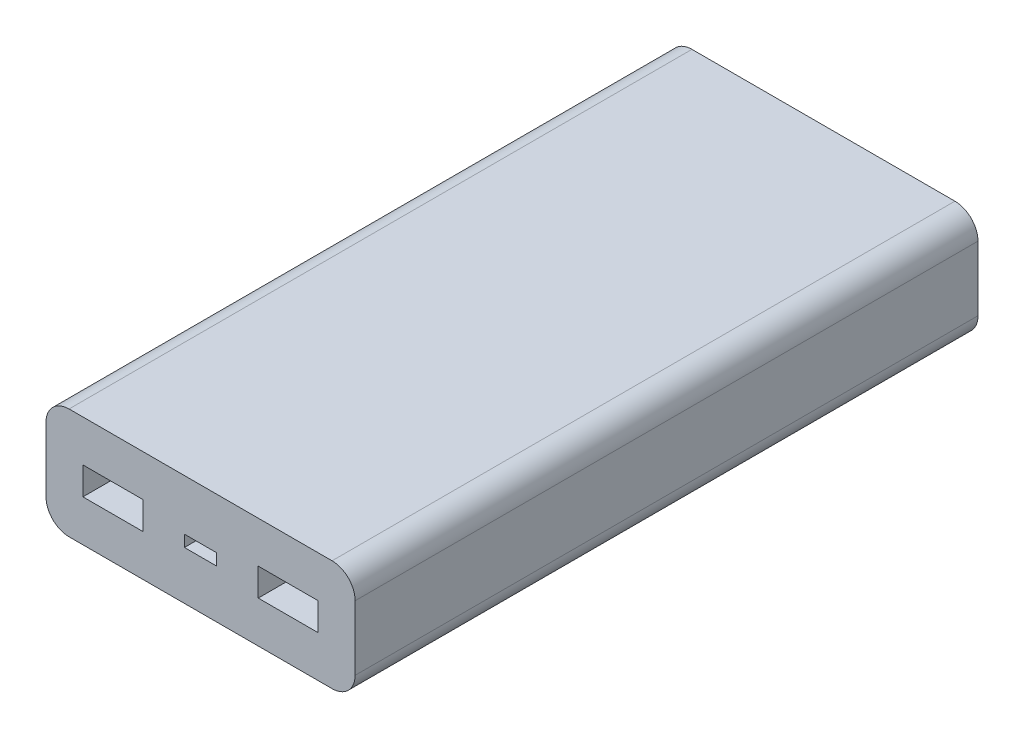
SolidWorks part; units mm, degrees
material "ABS"
ref_plane "Plan de face" through (0, 0, 0) normal (0, 0, 1) x (1, 0, 0)
ref_plane "Plan de dessus" through (0, 0, 0) normal (0, 1, 0) x (1, 0, 0)
ref_plane "Plan de droite" through (0, 0, 0) normal (1, 0, 0) x (0, 0, -1)
sketch "Esquisse1" plane through (0, 0, 0) normal (0, 0, 1) x (1, 0, 0)
  line L1 (0, 0) -> (67, 0)
  line L2 (0, 0) -> (0, 24)
  line L3 (0, 24) -> (67, 24)
  line L4 (67, 0) -> (67, 24)
  dimension "D1" = 67
  dimension "D2" = 24
extrude "Boss.-Extru.1" add sketch "Esquisse1" along normal blind 135
fillet "Congé1" radius 5 4 edges at (0, 0, 67.5) (67, 0, 67.5) (67, 24, 67.5) (0, 24, 67.5)
sketch "Esquisse2" plane through (0, 0, 135) normal (0, 0, 1) x (1, 0, 0)
  line L0 (0, 19) -> (0, 5) construction
  line L1 (8, 15) -> (21, 15)
  line L2 (8, 15) -> (8, 9)
  line L3 (8, 9) -> (21, 9)
  line L4 (21, 15) -> (21, 9)
  line L5 (46, 15) -> (59, 15)
  line L6 (46, 15) -> (46, 9)
  line L7 (46, 9) -> (59, 9)
  line L8 (59, 15) -> (59, 9)
  line L9 (30, 13) -> (37, 13)
  line L10 (30, 13) -> (30, 10.5)
  line L11 (30, 10.5) -> (37, 10.5)
  line L12 (37, 13) -> (37, 10.5)
  line L13 (67, 5) -> (67, 19) construction
  line L14 (62, 24) -> (5, 24) construction
  line L15 (5, 0) -> (62, 0) construction
  point P14 (0, 12)
  dimension "D1" = 8
  dimension "D2" = 8
  dimension "D3" = 9
  dimension "D4" = 9
  dimension "D5" = 9
  dimension "D6" = 9
  dimension "D7" = 13
  dimension "D8" = 13
  dimension "D9" = 11
  dimension "D10" = 2.5
  dimension "D11" = 30
  dimension "D12" = 30
extrude "Enlèv. mat.-Extru.1" cut sketch "Esquisse2" against normal blind 20
